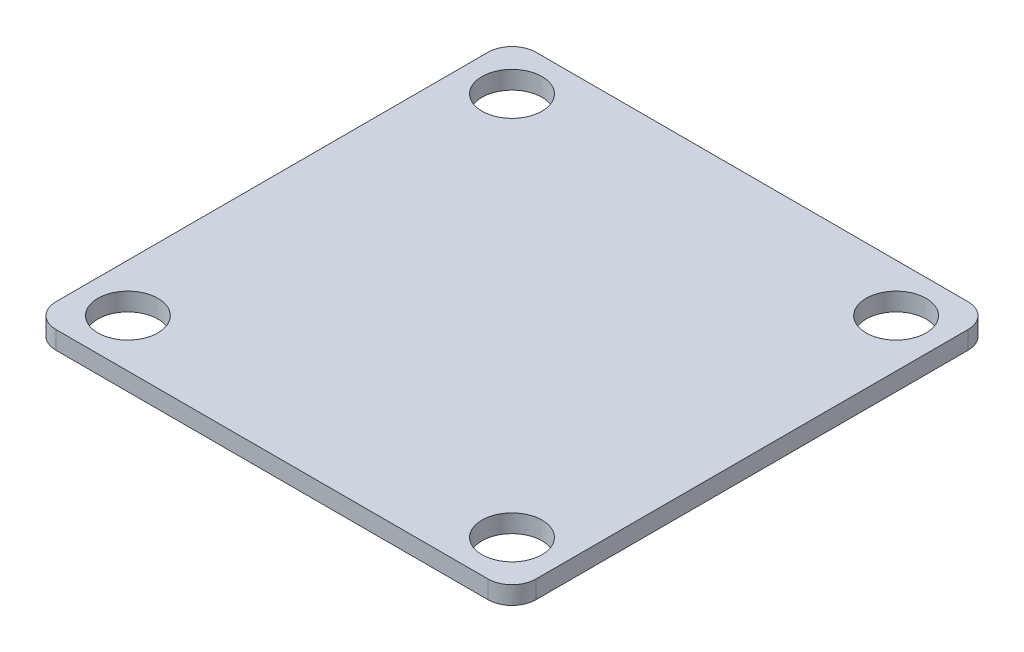
SolidWorks part; units mm, degrees
ref_plane "Plan de face" through (0, 0, 0) normal (0, 0, 1) x (1, 0, 0)
ref_plane "Plan de dessus" through (0, 0, 0) normal (0, 1, 0) x (1, 0, 0)
ref_plane "Plan de droite" through (0, 0, 0) normal (1, 0, 0) x (0, 0, -1)
sketch "Esquisse1" plane through (0, 0, 0) normal (0, 1, 0) x (1, 0, 0)
  line L1 (-36, 40) -> (36, 40)
  line L2 (-40, 36) -> (-40, -36)
  line L3 (-36, -40) -> (36, -40)
  line L4 (40, 36) -> (40, -36)
  line L5 (-40, 40) -> (40, -40) construction
  line L6 (-40, -40) -> (40, 40) construction
  arc A0 (36, 40) -> (40, 36) centre (36, 36) cw
  arc A1 (36, -40) -> (40, -36) centre (36, -36) ccw
  arc A2 (-40, -36) -> (-36, -40) centre (-36, -36) ccw
  arc A3 (-36, 40) -> (-40, 36) centre (-36, 36) ccw
  point P4 (0, 0)
  dimension "D2" = 4
  dimension "D1" = 80
extrude "Boss.-Extru.1" add sketch "Esquisse1" along normal blind 3
sketch "Esquisse2" plane through (0, 3, 0) normal (0, 1, 0) x (1, 0, 0)
  line L0 (36, 40) -> (-36, 40) construction
  line L1 (-40, 36) -> (-40, -36) construction
  circle A0 centre (-32, 32) radius 5
  circle A1 centre (32, 32) radius 5
  circle A2 centre (32, -32) radius 5
  circle A3 centre (-32, -32) radius 5
  point P12 (0, 0)
  dimension "D1" = 10
  dimension "D3" = 8
  dimension "D4" = 8
  dimension "D2" = 4
extrude "Enlèv. mat.-Extru.1" cut sketch "Esquisse2" against normal through all
